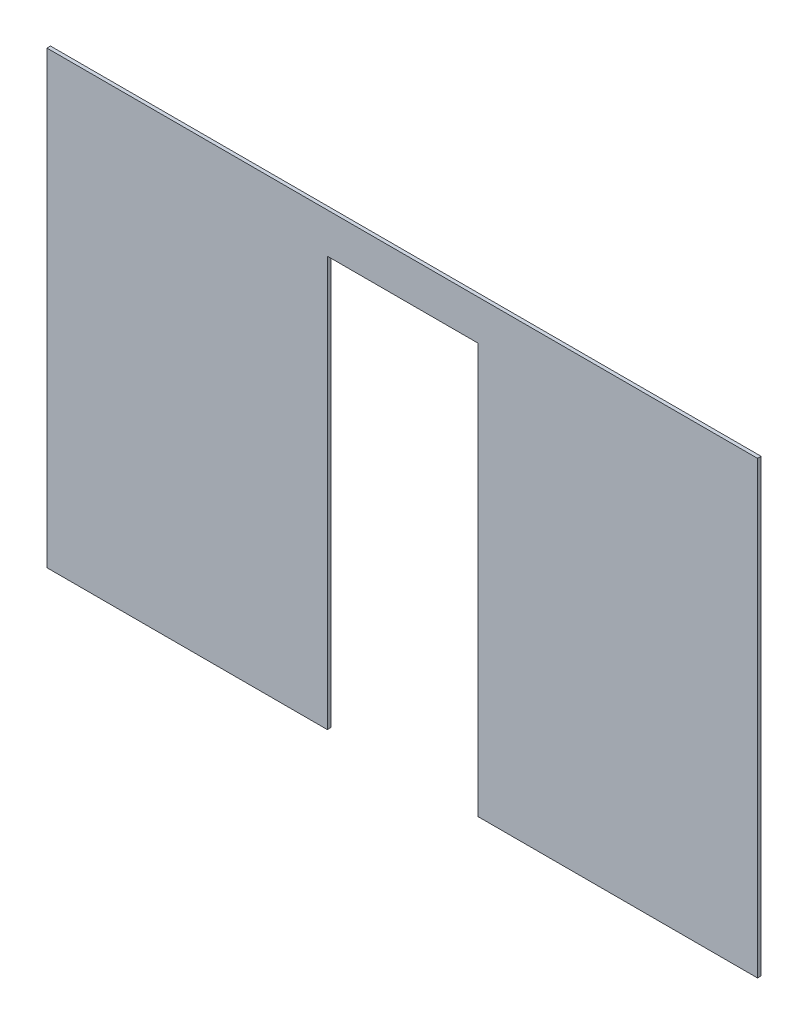
SolidWorks part; units mm, degrees
ref_plane "Alzado" through (0, 0, 0) normal (0, 0, 1) x (1, 0, 0)
ref_plane "Planta" through (0, 0, 0) normal (0, 1, 0) x (1, 0, 0)
ref_plane "Vista lateral" through (0, 0, 0) normal (1, 0, 0) x (0, 0, -1)
sketch "Croquis1" plane through (0, 0, 0) normal (0, 0, 1) x (1, 0, 0)
  line L1 (300, -190) -> (-300, -190)
  line L2 (300, -190) -> (300, 190)
  line L3 (300, 190) -> (-300, 190)
  line L4 (-300, -190) -> (-300, 190)
  line L5 (300, -190) -> (-300, 190) construction
  line L6 (300, 190) -> (-300, -190) construction
  point P0 (0, 0)
  dimension "D1" = 380
  dimension "D2" = 600
extrude "Saliente-Extruir1" add sketch "Croquis1" along normal blind 3
sketch "Croquis2" plane through (0, 0, 0) normal (0, 0, -1) x (-1, 0, 0)
  line L0 (300, -190) -> (-300, -190) construction
  line L1 (63.2652, -190) -> (-64.0932, -190)
  line L2 (63.2652, -190) -> (63.2652, 156.2138)
  line L3 (63.2652, 156.2138) -> (-64.0932, 156.2138)
  line L4 (-64.0932, -190) -> (-64.0932, 156.2138)
  dimension "D1" = 346.2138
  dimension "D2" = 127.3584
extrude "Cortar-Extruir1" cut sketch "Croquis2" against normal blind 10
